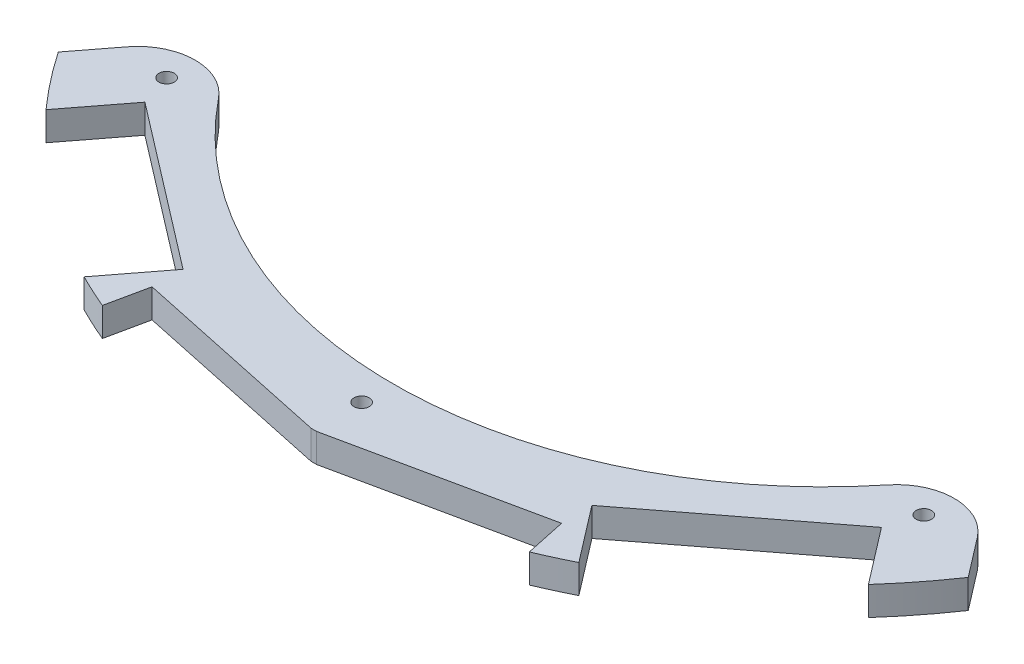
SolidWorks part; units mm, degrees
ref_plane "Front Plane" through (0, 0, 0) normal (0, 0, 1) x (1, 0, 0)
ref_plane "Top Plane" through (0, 0, 0) normal (0, 1, 0) x (1, 0, 0)
ref_plane "Right Plane" through (0, 0, 0) normal (1, 0, 0) x (0, 0, -1)
sketch "Sketch1" plane through (0, 0, 0) normal (0, 1, 0) x (1, 0, 0)
  line L0 (0, 0) -> (0, -152.4) construction
  line L1 (-152.4, -152.4) -> (152.4, -152.4) construction
  line L2 (-152.4, -152.4) -> (-152.4, 152.4) construction
  line L3 (-152.4, 152.4) -> (152.4, 152.4) construction
  line L4 (152.4, -152.4) -> (152.4, 152.4) construction
  line L5 (-152.4, -152.4) -> (152.4, 152.4) construction
  line L6 (-152.4, 152.4) -> (152.4, -152.4) construction
  line L7 (0, 0) -> (0, 102.2502) construction
  line L8 (0, 102.2502) -> (65.7158, 16.6077) construction
  line L9 (143.0285, -84.1481) -> (65.7158, 16.6077) construction
  line L10 (50.6024, 5.0108) -> (80.8292, 28.2047) construction
  line L11 (50.6024, 5.0108) -> (127.9151, -95.745) construction
  line L12 (127.9151, -95.745) -> (158.1419, -72.5512) construction
  line L13 (80.8292, 28.2047) -> (158.1419, -72.5512) construction
  line L14 (0, 102.2502) -> (50.1691, -133.7768) construction
  line L15 (50.1691, -133.7768) -> (68.8028, -129.8161) construction
  line L16 (68.8028, -129.8161) -> (42.398, -5.5913) construction
  line L17 (42.398, -5.5913) -> (5.1306, -13.5127) construction
  line L18 (5.1306, -13.5127) -> (31.5354, -137.7375) construction
  line L19 (31.5354, -137.7375) -> (50.1691, -133.7768) construction
  line L20 (0, 102.2502) -> (-65.7158, 16.6077) construction
  line L21 (-50.6024, 5.0108) -> (-80.8292, 28.2047) construction
  line L22 (-127.9151, -95.745) -> (-158.1419, -72.5512) construction
  line L23 (-80.8292, 28.2047) -> (-158.1419, -72.5512) construction
  line L24 (-50.6024, 5.0108) -> (-127.9151, -95.745) construction
  line L25 (-143.0285, -84.1481) -> (-65.7158, 16.6077) construction
  line L26 (-31.5354, -137.7375) -> (-50.1691, -133.7768) construction
  line L27 (-50.1691, -133.7768) -> (-68.8028, -129.8161) construction
  line L28 (-42.398, -5.5913) -> (-5.1306, -13.5127) construction
  line L29 (-5.1306, -13.5127) -> (-31.5354, -137.7375) construction
  line L30 (0, 102.2502) -> (-50.1691, -133.7768) construction
  line L31 (-68.8028, -129.8161) -> (-42.398, -5.5913) construction
  line L32 (0, 102.2502) -> (-152.4, -101.762) construction
  line L33 (0, 102.2502) -> (-112.0468, 18.8141) construction
  line L34 (0, 102.2502) -> (112.0468, 18.8141) construction
  line L35 (-105.9774, 26.7239) -> (-94.0975, 42.206) construction
  line L36 (94.0975, 42.206) -> (105.9774, 26.7239) construction
  line L37 (0, 102.2502) -> (152.4, -101.762) construction
  line L38 (-152.4, -50.962) -> (-152.4, -101.762) construction
  line L39 (152.4, -50.962) -> (152.4, -101.762) construction
  line L40 (72.5295, -129.0239) -> (45.3326, -1.0724) construction
  line L41 (45.3326, -1.0724) -> (0.6117, -10.5781) construction
  line L42 (0.6117, -10.5781) -> (27.8086, -138.5296) construction
  line L43 (81.5325, 33.5467) -> (161.1646, -70.2318) construction
  line L44 (45.2604, 5.7141) -> (81.5325, 33.5467) construction
  line L45 (45.2604, 5.7141) -> (124.8924, -98.0644) construction
  line L46 (98.1127, 11.939) -> (81.5325, 33.5467) construction
  line L47 (81.5325, 33.5467) -> (63.3964, 19.6304) construction
  line L48 (63.3964, 19.6304) -> (57.9845, 26.6833) construction
  line L49 (100.7298, 33.5626) -> (94.0975, 42.206)
  line L50 (91.0399, 21.1564) -> (81.5325, 33.5467)
  line L51 (81.5325, 33.5467) -> (63.3964, 19.6304)
  line L52 (54.7678, -6.6762) -> (45.2604, 5.7141)
  line L53 (45.2604, 5.7141) -> (63.3964, 19.6304)
  line L54 (47.2595, -10.1376) -> (45.3326, -1.0724)
  line L55 (45.3326, -1.0724) -> (0.6117, -10.5781)
  line L56 (-0.6117, -10.5781) -> (0.6117, -10.5781)
  line L57 (-100.7298, 33.5626) -> (-94.0975, 42.206)
  line L58 (-91.0399, 21.1564) -> (-81.5325, 33.5467)
  line L59 (-81.5325, 33.5467) -> (-63.3964, 19.6304)
  line L60 (-45.2604, 5.7141) -> (-63.3964, 19.6304)
  line L61 (-54.7678, -6.6762) -> (-45.2604, 5.7141)
  line L62 (-47.2595, -10.1376) -> (-45.3326, -1.0724)
  line L63 (-45.3326, -1.0724) -> (-0.6117, -10.5781)
  circle A0 centre (0, 102.2502) radius 12.7 construction
  arc A1 (-152.4, -101.762) -> (152.4, -101.762) centre (0, 102.2502) ccw construction
  arc A2 (-152.4, -50.962) -> (152.4, -50.962) centre (0, 102.2502) ccw construction
  arc A3 (-105.492, 10.6668) -> (105.492, 10.6668) centre (0, 102.2502) ccw construction
  arc A4 (-74.137, 42.4484) -> (74.137, 42.4484) centre (0, 102.2502) ccw construction
  arc A5 (74.137, 42.4484) -> (94.0975, 42.206) centre (84.0219, 34.4748) cw construction
  arc A6 (-74.137, 42.4484) -> (-94.0975, 42.206) centre (-84.0219, 34.4748) ccw construction
  arc A7 (105.9774, 26.7239) -> (105.492, 10.6668) centre (95.9018, 18.9926) cw construction
  arc A8 (-105.9774, 26.7239) -> (-105.492, 10.6668) centre (-95.9018, 18.9926) ccw construction
  arc A9 (-97.8072, 11.6082) -> (110.1733, 27.1232) centre (0, 102.2502) ccw construction
  circle A10 centre (102.87, 17.3975) radius 1.7005 construction
  circle A11 centre (83.82, 40.64) radius 1.7005
  circle A12 centre (25.4, 2.54) radius 1.7005 construction
  circle A13 centre (0, -30.48) radius 1.7005 construction
  circle A14 centre (-102.87, 17.3975) radius 1.7005 construction
  circle A15 centre (-83.82, 40.64) radius 1.7005
  circle A16 centre (-25.4, 2.54) radius 1.7005 construction
  arc A17 (74.137, 42.4484) -> (-74.137, 42.4484) centre (0, 102.2502) cw
  arc A18 (-89.4237, 19.3775) -> (100.7298, 33.5626) centre (0, 102.2502) ccw construction
  arc A19 (91.0399, 21.1564) -> (100.7298, 33.5626) centre (0, 102.2502) ccw
  arc A20 (94.0975, 42.206) -> (74.137, 42.4484) centre (84.0219, 34.4748) ccw
  arc A21 (54.7678, -6.6762) -> (47.2595, -10.1376) centre (0, 102.2502) cw
  circle A22 centre (0, 0) radius 1.7005
  circle A23 centre (-83.82, 40.64) radius 1.7005 construction
  arc A24 (-94.0975, 42.206) -> (-74.137, 42.4484) centre (-84.0219, 34.4748) cw
  arc A25 (-91.0399, 21.1564) -> (-100.7298, 33.5626) centre (0, 102.2502) cw
  arc A26 (-54.7678, -6.6762) -> (-47.2595, -10.1376) centre (0, 102.2502) ccw
  point P0 (0, 0)
  point P60 (98.1127, 11.939)
  dimension "D4" = 25.4
  dimension "D19" = 12.7
  dimension "D13" = 139.7
  dimension "D14" = 95.25
  dimension "D18" = 12.7
  dimension "D21" = 133.35
  dimension "D22" = 3.4011
  dimension "D28" = 30.48
  dimension "D17" = 3.4011
  dimension "D1" = 304.8
  dimension "D2" = 304.8
  dimension "D3" = 50.1498
  dimension "D5" = 127
  dimension "D6" = 38.1
  dimension "D7" = 37.5
  dimension "D8" = 107.95
  dimension "D9" = 12
  dimension "D10" = 38.1
  dimension "D11" = 127
  dimension "D12" = 114.3
  dimension "D15" = 19.05
  dimension "D16" = 50.8
  dimension "D20" = 3.81
  dimension "D23" = 102.87
  dimension "D24" = 83.82
  dimension "D25" = 40.64
  dimension "D26" = 25.4
  dimension "D27" = 2.54
  dimension "D30" = 11.8077
  dimension "D29" = 11.43
extrude "Boss-Extrude1" add sketch "Sketch1" along normal blind 6.35
